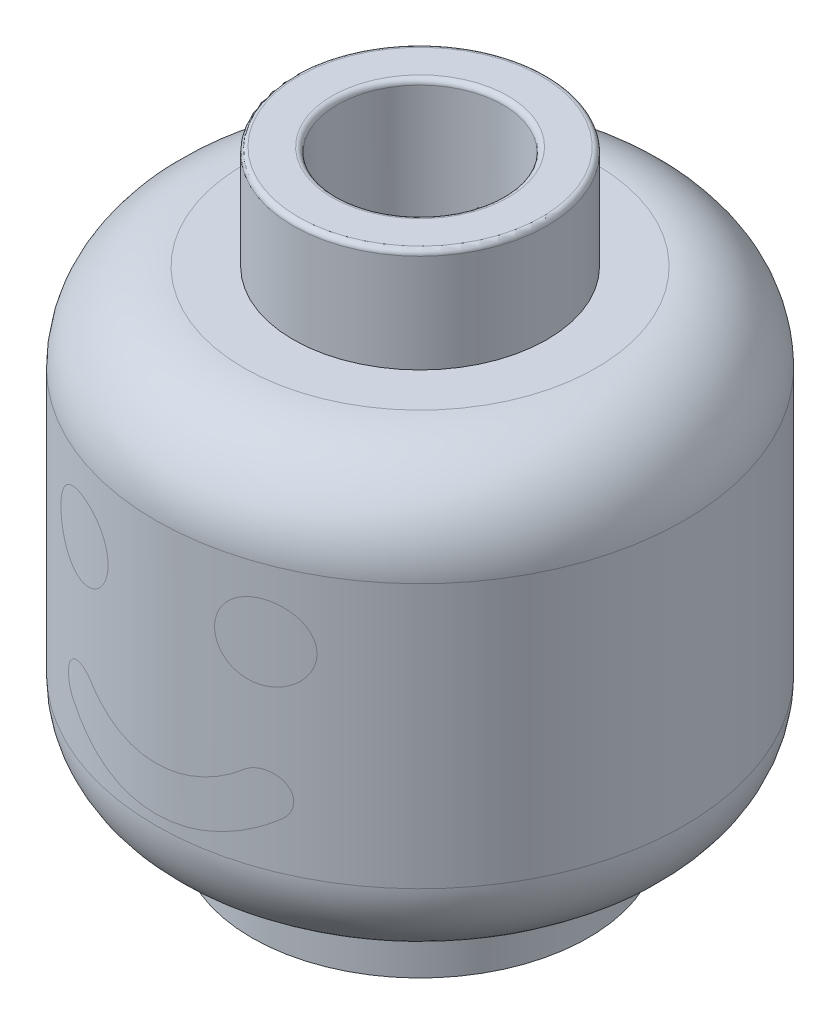
SolidWorks part; units mm, degrees
ref_plane "Front Plane" through (0, 0, 0) normal (0, 0, 1) x (1, 0, 0)
ref_plane "Top Plane" through (0, 0, 0) normal (0, 1, 0) x (1, 0, 0)
ref_plane "Right Plane" through (0, 0, 0) normal (1, 0, 0) x (0, 0, -1)
sketch "Sketch2" plane through (0, 0, 0) normal (0, 1, 0) x (1, 0, 0)
  circle A0 centre (0, 0) radius 5.1
  dimension "D1" = 10.2
extrude "Boss-Extrude1" add sketch "Sketch2" along normal blind 8.5
sketch "Sketch3" plane through (0, 8.5, 0) normal (0, 1, 0) x (1, 0, 0)
  circle A2 centre (0, 0) radius 2.45
  dimension "D2" = 4.9
extrude "Boss-Extrude2" add sketch "Sketch3" along normal blind 2 contours A2
sketch "Sketch4" plane through (0, 10.5, 0) normal (0, 1, 0) x (1, 0, 0)
  circle A0 centre (0, 0) radius 1.6
  dimension "D1" = 3.2
extrude "Cut-Extrude1" cut sketch "Sketch4" against normal blind 2 contours A0
fillet "Fillet1" radius 1.7 2 edges at (0, 0, 5.1) (0, 8.5, 5.1)
fillet "Fillet2" radius 0.1 2 edges at (0, 10.5, 1.6) (0, 10.5, 2.45)
sketch "Sketch5" plane through (0, 0, 0) normal (0, -1, 0) x (1, 0, 0)
  circle A0 centre (0, 0) radius 3.25
  dimension "D1" = 6.5
extrude "Boss-Extrude3" add sketch "Sketch5" along normal blind 1.1
sketch "Sketch6" plane through (0, -1.1, 0) normal (0, -1, 0) x (1, 0, 0)
  circle A0 centre (0, 0) radius 2.45
  dimension "D1" = 4.9
extrude "Cut-Extrude2" cut sketch "Sketch6" against normal blind 8.5
ref_plane "Plane3" through (0, 8.5, 0) normal (0, 1, 0) x (1, 0, 0)
sketch "Sketch11" plane through (0, 8.5, 0) normal (0, 1, 0) x (1, 0, 0)
  line L0 (0, 0) -> (0, -5.9398) construction
  line L1 (0, 0) -> (0, 5.6442) construction
  line L2 (0, 0) -> (6.6013, 0) construction
  line L3 (0, 0) -> (-8.0229, 0) construction
  line L4 (-0.42, 1.5439) -> (-0.42, 0.2406)
  line L5 (0.42, 1.5439) -> (0.42, 0.2406)
  line L6 (-0.42, 0.2406) -> (-1.5466, -0.4098)
  line L7 (0, -0.4869) -> (-1.1258, -1.1369)
  line L8 (0, -0.4869) -> (1.1258, -1.1369)
  line L9 (0.42, 0.2406) -> (1.5466, -0.4098)
  circle A0 centre (0, 0) radius 1.6 construction
  circle A1 centre (0, 0) radius 1.6
  dimension "D12" = 3.2
  dimension "D1" = 0.42
  dimension "D2" = 0.42
  dimension "D3" = 0.84
  dimension "D4" = 0.84
  dimension "D5" = 120
  dimension "D6" = 120
  dimension "D7" = 1.3033
  dimension "D8" = 1.3009
  dimension "D9" = 1.3
  dimension "D10" = 1.3
  dimension "D11" = 1.3033
extrude "Cut-Extrude3" cut sketch "Sketch11" against normal blind 1.1 contours L4 A1 L6 | L9 A1 L5 | L7 A1 L8
ref_plane "Plane5" through (0, 0, -5.1) normal (0, 0, 1) x (1, 0, 0)
sketch "Sketch13" plane through (0, 0, -5.1) normal (0, 0, 1) x (1, 0, 0)
  line L0 (0, 0) -> (0, 10.9801) construction
  line L1 (0, 5.49) -> (-8.2535, 5.49) construction
  line L2 (0, 5.49) -> (7.6097, 5.49) construction
  line L3 (0, 2.3178) -> (8.5625, 2.3178) construction
  line L4 (0, 2.3178) -> (-6.5627, 2.3178) construction
  circle A0 centre (-1.75, 5.49) radius 0.7219
  circle A1 centre (1.75, 5.49) radius 0.7219
  arc A2 (-1.75, 2.9429) -> (1.75, 2.9429) centre (0, 5.0799) ccw construction
  arc A3 (-2.0191, 2.6143) -> (2.0191, 2.6143) centre (0, 5.0799) ccw
  arc A4 (-1.4809, 3.2715) -> (1.4809, 3.2715) centre (0, 5.0799) ccw
  arc A5 (-1.4809, 3.2715) -> (-2.0191, 2.6143) centre (-1.75, 2.9429) ccw
  arc A6 (2.0191, 2.6143) -> (1.4809, 3.2715) centre (1.75, 2.9429) ccw
  point P13 (0, 2.3178)
  point P18 (0, 0)
  dimension "D1" = 1.4438
  dimension "D6" = 1.4438
  dimension "D2" = 1.75
  dimension "D3" = 2.5472
  dimension "D4" = 2.5472
  dimension "D5" = 3.1723
split line "Split Line1"
